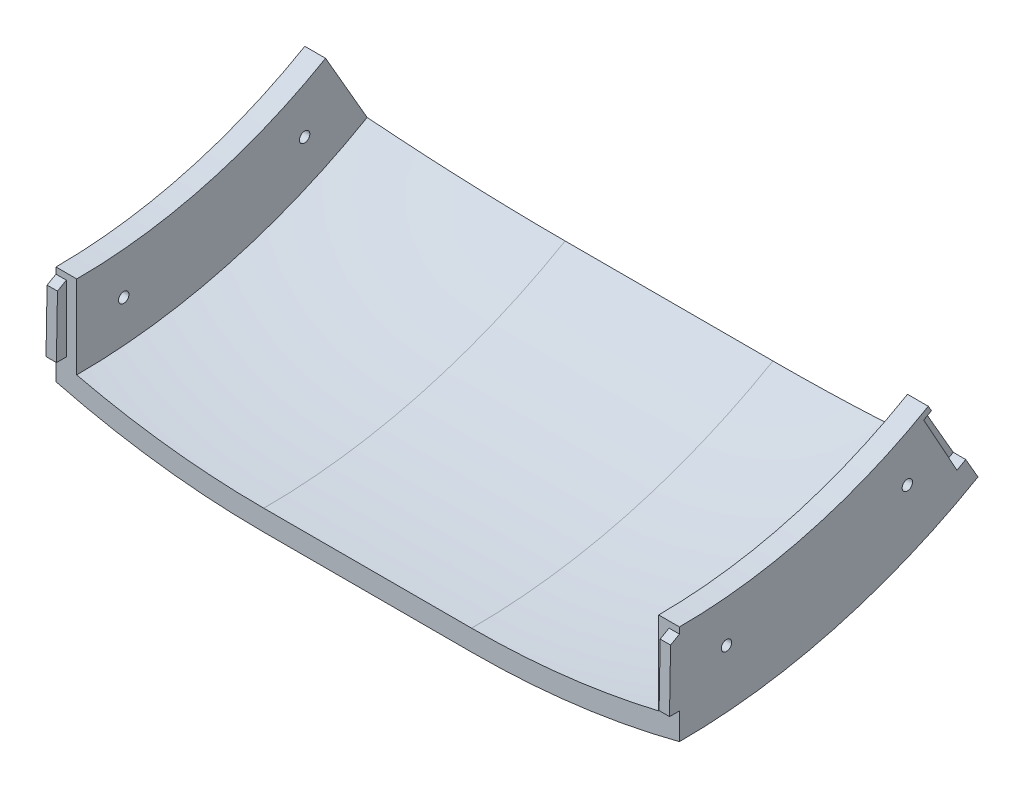
SolidWorks part; units mm, degrees
material "ABS"
ref_plane "Plan de face" through (0, 0, 0) normal (0, 0, 1) x (1, 0, 0)
ref_plane "Plan de dessus" through (0, 0, 0) normal (0, 1, 0) x (1, 0, 0)
ref_plane "Plan de droite" through (0, 0, 0) normal (1, 0, 0) x (0, 0, -1)
sketch "Esquisse1" plane through (0, 0, 0) normal (0, 0, 1) x (1, 0, 0)
  line L0 (0, 0) -> (0, -300) construction
  line L1 (-50, -300) -> (50, -300)
  line L2 (150, -287.2983) -> (150, -239.4733)
  line L3 (150, -239.4733) -> (140, -239.4733)
  line L4 (140, -239.4733) -> (140, -279.4733)
  line L6 (50, -290) -> (-50, -290)
  line L8 (0, 0) -> (62.0401, 0) construction
  line L9 (-150, -239.4733) -> (-140, -239.4733)
  line L10 (-150, -287.2983) -> (-150, -239.4733)
  line L11 (-140, -239.4733) -> (-140, -279.4733)
  arc A0 (50, -300) -> (150, -287.2983) centre (50, 100) ccw
  arc A1 (50, -290) -> (140, -279.4733) centre (50, 100) ccw
  arc A2 (-50, -300) -> (-150, -287.2983) centre (-50, 100) cw
  arc A3 (-50, -290) -> (-140, -279.4733) centre (-50, 100) cw
  point P21 (0, -290)
  dimension "D3" = 100
  dimension "D8" = 390
  dimension "D9" = 400
  dimension "D1" = 300
  dimension "D2" = 50
  dimension "D4" = 40
  dimension "D5" = 10
  dimension "D6" = 10
  dimension "D7" = 50
revolve "Révolution3" add sketch "Esquisse1" angle 30 about L8
sketch "Esquisse2" plane through (0, 0, 0) normal (0, 0, 1) x (1, 0, 0)
  line L0 (-150, -239.4733) -> (-150, -287.2983) construction
  line L1 (-150, -242.4733) -> (-145, -242.4733)
  line L2 (-150, -242.4733) -> (-150, -274.4733)
  line L3 (-150, -274.4733) -> (-145, -274.4733)
  line L4 (-145, -242.4733) -> (-145, -274.4733)
  line L5 (-140, -279.4733) -> (-140, -242.031) construction
  line L6 (-140, -239.4733) -> (-150, -239.4733) construction
  line L7 (0, 0) -> (0, -300) construction
  line L8 (150, -274.4733) -> (145, -274.4733)
  line L9 (145, -242.4733) -> (145, -274.4733)
  line L10 (150, -242.4733) -> (150, -274.4733)
  line L11 (150, -242.4733) -> (145, -242.4733)
  line L12 (-50, -300) -> (50, -300) construction
  line L13 (-163.4974, 0) -> (155.0501, 0) construction
  dimension "D1" = 0
  dimension "D2" = 5
  dimension "D3" = 3
  dimension "D4" = 32
  dimension "D5" = 300
revolve "Révolution4" add sketch "Esquisse2" angle 1 about L13
sketch "Esquisse3" plane through (0, 0, 0) normal (0, 0.5, -0.866) x (1, 0, 0)
  line L0 (-150, 239.4733) -> (-150, 287.2983) construction
  line L1 (-150, 275.4733) -> (-144, 275.4733)
  line L2 (-150, 275.4733) -> (-150, 242.4733)
  line L3 (-150, 242.4733) -> (-144, 242.4733)
  line L4 (-144, 275.4733) -> (-144, 242.4733)
  line L5 (-140, 242.031) -> (-140, 279.4733) construction
  line L6 (-140, 239.4733) -> (-150, 239.4733) construction
  line L7 (0, 300) -> (0, 0) construction
  line L8 (-50, 300) -> (50, 300) construction
  line L9 (150, 242.4733) -> (144, 242.4733)
  line L10 (144, 275.4733) -> (144, 242.4733)
  line L11 (150, 275.4733) -> (150, 242.4733)
  line L12 (150, 275.4733) -> (144, 275.4733)
  line L13 (-66.7687, 0) -> (66.5189, 0) construction
  dimension "D1" = 0
  dimension "D2" = 4
  dimension "D3" = 3
  dimension "D4" = 33
  dimension "D5" = 300
revolve "Enlèvement de matière-Révolution1" cut sketch "Esquisse3" angle 1 about L13
ref_plane "Plan1" through (0, -207.39, -119.7367) normal (0, -0.866, -0.5) x (-1, 0, 0)
sketch "Esquisse4" plane through (-150, 0, 0) normal (-1, 0, 0) x (0, 0, 1)
  line L0 (0, -242.4733) -> (4.2746, -244.8918)
  line L1 (4.2317, -242.4364) -> (4.7902, -274.4315) construction
  line L2 (4.2746, -244.8918) -> (4.2317, -242.4364)
  line L3 (4.2317, -242.4364) -> (0, -242.4733)
  arc A0 (0, -242.4733) -> (4.2317, -242.4364) centre (0, 0) ccw construction
  dimension "D1" = 30
extrude "Enlèv. mat.-Extru.1" cut sketch "Esquisse4" against normal blind 300
sketch "Esquisse5" plane through (-150, 0, 0) normal (-1, 0, 0) x (0, 0, 1)
  line L0 (0, 0) -> (0, -287.2983) construction
  line L1 (0, 0) -> (-22.6143, -258.4826) construction
  line L2 (-109.6568, -235.1597) -> (0, 0) construction
  line L3 (-129.4867, -224.2775) -> (0, 0) construction
  line L4 (-121.2367, -209.9881) -> (-137.7367, -238.5669) construction
  circle A1 centre (-22.6143, -258.4826) radius 2.5
  arc A2 (-139.7367, -242.031) -> (0, -279.4733) centre (0, 0) ccw construction
  circle A3 centre (-109.6568, -235.1597) radius 2.5
  dimension "D1" = 259.47
  dimension "D2" = 5
  dimension "D4" = 5
  dimension "D3" = 5
  dimension "D5" = 5
  dimension "D6" = 259.47
extrude "Enlèv. mat.-Extru.2" cut sketch "Esquisse5" against normal blind 300
